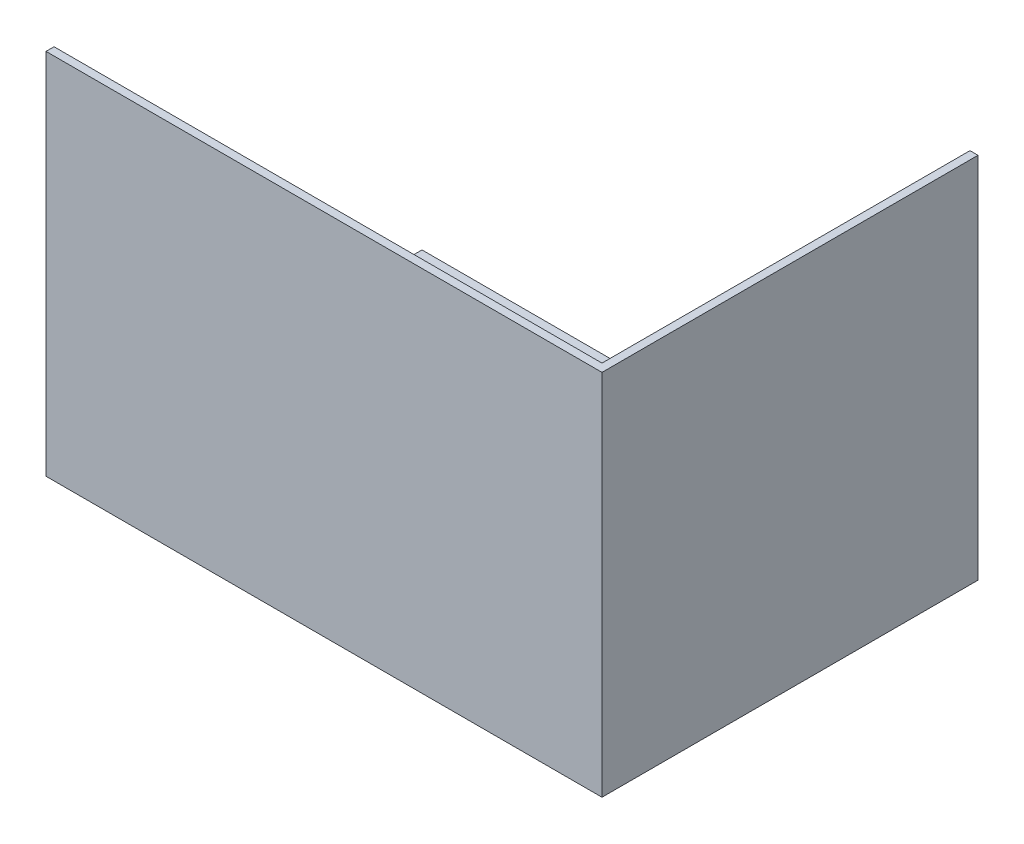
SolidWorks part; units mm, degrees
ref_plane "Front Plane" through (0, 0, 0) normal (0, 0, 1) x (1, 0, 0)
ref_plane "Top Plane" through (0, 0, 0) normal (0, 1, 0) x (1, 0, 0)
ref_plane "Right Plane" through (0, 0, 0) normal (1, 0, 0) x (0, 0, -1)
sketch "Sketch1" plane through (0, 0, 0) normal (0, 1, 0) x (1, 0, 0)
  line L1 (0, 0) -> (235.4072, 0)
  line L2 (0, 0) -> (0, 159.2072)
  line L3 (0, 159.2072) -> (235.4072, 159.2072)
  line L4 (235.4072, 0) -> (235.4072, 159.2072)
  dimension "D1" = 235.4072
  dimension "D2" = 159.2072
extrude "Boss-Extrude1" add sketch "Sketch1" along normal blind 3.4036
sketch "Sketch2" plane through (0, 3.4036, 0) normal (0, 1, 0) x (1, 0, 0)
  line L0 (0, 159.2072) -> (0, 0) construction
  line L1 (0, 3.4036) -> (235.4072, 3.4036)
  line L2 (0, 3.4036) -> (0, 0)
  line L3 (0, 0) -> (235.4072, 0)
  line L4 (235.4072, 3.4036) -> (235.4072, 0)
  line L6 (232.0036, 3.4036) -> (235.4072, 3.4036)
  line L7 (232.0036, 3.4036) -> (232.0036, 159.2072)
  line L8 (232.0036, 159.2072) -> (235.4072, 159.2072)
  line L9 (235.4072, 3.4036) -> (235.4072, 159.2072)
  dimension "D1" = 3.4036
  dimension "D2" = 3.4036
extrude "Boss-Extrude2" add sketch "Sketch2" along normal blind 152.4 contours L6 L7 L8 L9 | L4 L3 L2 L1
